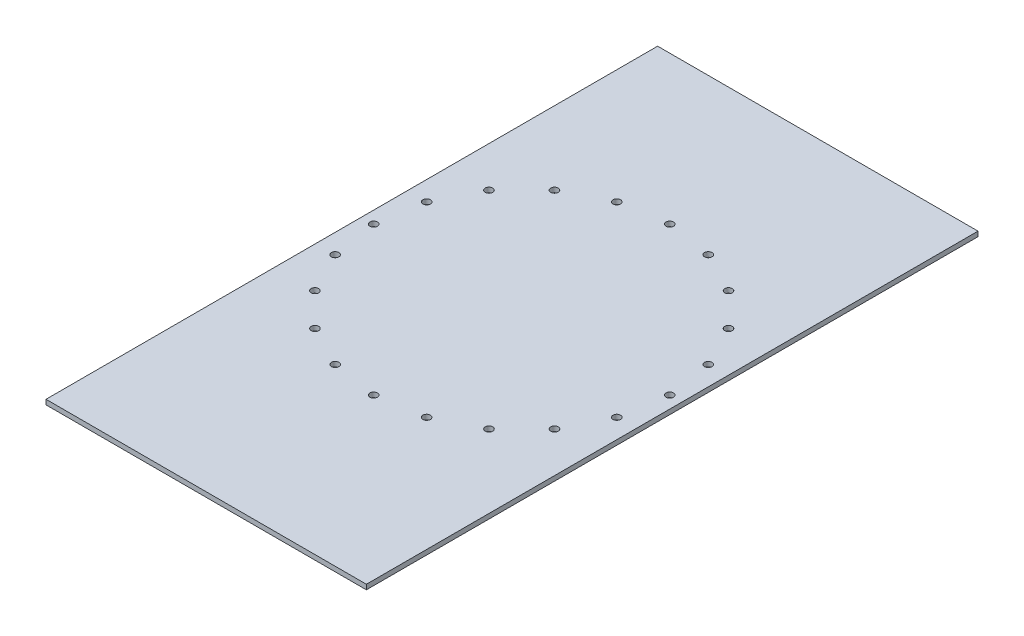
SolidWorks part; units mm, degrees
ref_plane "Plan de face" through (0, 0, 0) normal (0, 0, 1) x (1, 0, 0)
ref_plane "Plan de dessus" through (0, 0, 0) normal (0, 1, 0) x (1, 0, 0)
ref_plane "Plan de droite" through (0, 0, 0) normal (1, 0, 0) x (0, 0, -1)
sketch "Esquisse1" plane through (0, 0, 0) normal (0, 1, 0) x (1, 0, 0)
  line L1 (0, 0) -> (660, 0)
  line L2 (0, 0) -> (0, 1260)
  line L3 (0, 1260) -> (660, 1260)
  line L4 (660, 0) -> (660, 1260)
  dimension "D1" = 1260
  dimension "D2" = 660
extrude "Boss.-Extru.1" add sketch "Esquisse1" along normal blind 10
sketch "Esquisse2" plane through (0, 10, 0) normal (0, 1, 0) x (1, 0, 0)
  line L0 (330, 1260) -> (330, 0) construction
  line L1 (660, 1260) -> (0, 1260) construction
  line L2 (0, 0) -> (660, 0) construction
  line L3 (330, 650) -> (25, 650) construction
  circle A0 centre (25, 650) radius 7.75
  circle A1 centre (330, 650) radius 305 construction
  circle A2 centre (39.9278, 744.2502) radius 7.75
  circle A3 centre (83.2498, 829.2745) radius 7.75
  circle A4 centre (150.7255, 896.7502) radius 7.75
  circle A5 centre (235.7498, 940.0722) radius 7.75
  circle A6 centre (330, 955) radius 7.75
  circle A7 centre (424.2502, 940.0722) radius 7.75
  circle A8 centre (509.2745, 896.7502) radius 7.75
  circle A9 centre (576.7502, 829.2745) radius 7.75
  circle A10 centre (620.0722, 744.2502) radius 7.75
  circle A11 centre (635, 650) radius 7.75
  circle A12 centre (620.0722, 555.7498) radius 7.75
  circle A13 centre (576.7502, 470.7255) radius 7.75
  circle A14 centre (509.2745, 403.2498) radius 7.75
  circle A15 centre (424.2502, 359.9278) radius 7.75
  circle A16 centre (330, 345) radius 7.75
  circle A17 centre (235.7498, 359.9278) radius 7.75
  circle A18 centre (150.7255, 403.2498) radius 7.75
  circle A19 centre (83.2498, 470.7255) radius 7.75
  circle A20 centre (39.9278, 555.7498) radius 7.75
  point P6 (330, 650)
  point P52 (330, 650)
  dimension "D2" = 15.5
  dimension "D1" = 305
  dimension "D4" = 650
  dimension "D3" = 20
extrude "Enlèv. mat.-Extru.1" cut sketch "Esquisse2" against normal blind 10
